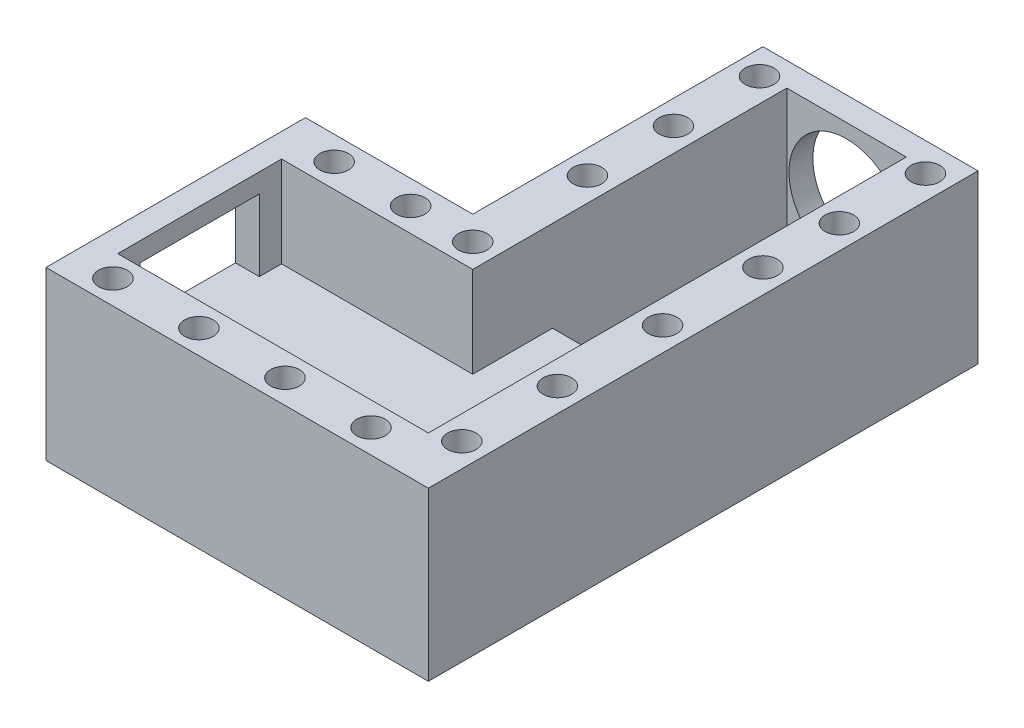
SolidWorks part; units mm, degrees
ref_plane "Спереди" through (0, 0, 0) normal (0, 0, 1) x (1, 0, 0)
ref_plane "Сверху" through (0, 0, 0) normal (0, 1, 0) x (1, 0, 0)
ref_plane "Справа" through (0, 0, 0) normal (1, 0, 0) x (0, 0, -1)
sketch "Эскиз1" plane through (0, 0, 0) normal (0, 1, 0) x (1, 0, 0)
  line L1 (-30, -18.4615) -> (35, -18.4615)
  line L2 (-30, -18.4615) -> (-30, 15.8242)
  line L3 (-30, 15.8242) -> (10, 15.8242)
  line L4 (35, -18.4615) -> (35, 21.5385)
  line L5 (-30, -18.4615) -> (35, 21.5385) construction
  line L6 (-30, 15.8242) -> (35, -18.4615) construction
  line L8 (35, 21.5385) -> (35, 81.5385)
  line L9 (35, 81.5385) -> (10, 81.5385)
  line L10 (10, 15.8242) -> (10, 81.5385)
  line L14 (-25.9919, 25.8242) -> (0, 25.8242)
  line L15 (0, 25.8242) -> (0, 86.5385)
  line L19 (0, 86.5385) -> (45, 86.5385)
  line L20 (45, 86.5385) -> (45, -28.4615)
  line L21 (45, -28.4615) -> (-35, -28.4615)
  line L22 (-35, -28.4615) -> (-35, 25.8242)
  line L23 (-35, 25.8242) -> (-25.9919, 25.8242)
  point P0 (0, 0)
  dimension "D1" = 40
  dimension "D2" = 65
  dimension "D3" = 60
  dimension "D4" = 25
  dimension "D5" = 10
  dimension "D6" = 5
  dimension "D7" = 10
  dimension "D8" = 10
  dimension "D9" = 5
  dimension "D10" = 10
extrude "Бобышка-Вытянуть1" add sketch "Эскиз1" along normal blind 35
sketch "Эскиз3" plane through (0, 0, 0) normal (0, -1, 0) x (1, 0, 0)
  line L0 (35, -81.5385) -> (35, 18.4615)
  line L1 (35, 18.4615) -> (-30, 18.4615)
  line L2 (-30, 18.4615) -> (-30, -15.8242)
  line L3 (-30, -15.8242) -> (10, -15.8242)
  line L4 (10, -15.8242) -> (10, -81.5385)
  line L5 (10, -81.5385) -> (35, -81.5385)
extrude "Бобышка-Вытянуть2" add sketch "Эскиз3" against normal blind 5
sketch "Эскиз4" plane through (0, 35, 0) normal (0, 1, 0) x (1, 0, 0)
  line L0 (35, 81.5385) -> (35, -28.4615) construction
  line L1 (-35, -28.4615) -> (45, -28.4615) construction
  line L2 (35, -28.4615) -> (35, 86.5385) construction
  line L3 (45, 86.5385) -> (0, 86.5385) construction
  line L4 (35, 86.5385) -> (45, 86.5385) construction
  line L5 (35, -28.4615) -> (45, -28.4615) construction
  line L6 (35, -18.4615) -> (-35, -18.4615) construction
  line L7 (35, -18.4615) -> (-30, -18.4615) construction
  line L8 (-35, 25.8242) -> (-35, -28.4615) construction
  line L9 (-35, -18.4615) -> (-35, -28.4615) construction
  line L10 (-35, -23.4615) -> (45, -23.4615) construction
  line L11 (45, -28.4615) -> (45, 86.5385) construction
  line L12 (40, 86.5385) -> (40, -28.4615) construction
  line L13 (10, 15.8242) -> (10, 86.5385) construction
  line L14 (10, 86.5385) -> (0, 86.5385) construction
  line L15 (0, 86.5385) -> (0, 15.8242) construction
  line L16 (10, 15.8242) -> (-30, 15.8242) construction
  line L17 (0, 15.8242) -> (10, 15.8242) construction
  line L18 (10, 15.8242) -> (-35, 15.8242) construction
  line L19 (-35, 15.8242) -> (-35, 25.8242) construction
  line L20 (-35, 25.8242) -> (10, 25.8242) construction
  line L21 (5, 86.5385) -> (5, 15.8242) construction
  line L22 (-35, 20.8242) -> (10, 20.8242) construction
  circle A0 centre (40, 80.5385) radius 3
  circle A1 centre (40, 62.5385) radius 3
  circle A2 centre (40, 46.5385) radius 3
  circle A3 centre (40, 25.5385) radius 3
  circle A4 centre (40, 3.5385) radius 3
  circle A5 centre (40, -16.4615) radius 3
  circle A6 centre (5, 80.8242) radius 3
  circle A7 centre (5, 62.8242) radius 3
  circle A8 centre (5, 44.8242) radius 3
  circle A9 centre (-24, 20.8242) radius 3
  circle A10 centre (-8, 20.8242) radius 3
  circle A11 centre (5, 20.8242) radius 3
  circle A12 centre (-26, -23.4615) radius 3
  circle A13 centre (-8, -23.4615) radius 3
  circle A14 centre (10, -23.4615) radius 3
  circle A15 centre (28, -23.4615) radius 3
  dimension "D1" = 6
  dimension "D2" = 6
  dimension "D3" = 6
  dimension "D4" = 6
  dimension "D5" = 6
  dimension "D6" = 18
  dimension "D7" = 18
  dimension "D8" = 13
  dimension "D9" = 16
  dimension "D10" = 18
  dimension "D11" = 16
  dimension "D12" = 21
  dimension "D13" = 22
  dimension "D14" = 20
  dimension "D15" = 18
  dimension "D16" = 18
  dimension "D17" = 18
  dimension "D18" = 12
  dimension "D19" = 17
  dimension "D21" = 5
  dimension "D22" = 24
  dimension "D20" = 5
extrude "Вырез-Вытянуть1" cut sketch "Эскиз4" against normal blind 20
sketch "Эскиз6" plane through (0, 5, 0) normal (0, 1, 0) x (1, 0, 0)
  line L0 (35, 81.5385) -> (35, -18.4615) construction
  line L1 (10, 15.8242) -> (35, 15.8242)
  line L2 (10, 15.8242) -> (10, 32.5031)
  line L3 (10, 32.5031) -> (35, 32.5031)
  line L4 (35, 15.8242) -> (35, 32.5031)
extrude "Бобышка-Вытянуть3" add sketch "Эскиз6" along normal blind 11
sketch "Эскиз7" plane through (0, 5, 0) normal (0, 1, 0) x (1, 0, 0)
  line L1 (35, 15.8242) -> (-30, 15.8242)
  line L2 (35, 15.8242) -> (35, -18.4615)
  line L3 (35, -18.4615) -> (-30, -18.4615)
  line L4 (-30, 15.8242) -> (-30, -18.4615)
extrude "Бобышка-Вытянуть4" add sketch "Эскиз7" along normal blind 11
sketch "Эскиз8" plane through (0, 0, -81.5385) normal (0, 0, 1) x (1, 0, 0)
  line L0 (22.5, 35) -> (22.5, 5) construction
  line L1 (35, 35) -> (10, 35) construction
  line L2 (10, 5) -> (35, 5) construction
  circle A0 centre (22.5, 20) radius 12.0525
extrude "Вырез-Вытянуть2" cut sketch "Эскиз8" against normal blind 11
sketch "Эскиз9" plane through (-30, 0, 0) normal (1, 0, 0) x (0, 0, -1)
  line L0 (-1.3187, 35) -> (-1.3187, 16) construction
  line L1 (15.8242, 35) -> (-18.4615, 35) construction
  line L2 (15.8242, 16) -> (-18.4615, 16) construction
  line L4 (-13.8187, 31) -> (11.1813, 31)
  line L5 (-13.8187, 31) -> (-13.8187, 16)
  line L6 (-13.8187, 16) -> (11.1813, 16)
  line L7 (11.1813, 31) -> (11.1813, 16)
  line L8 (-13.8187, 31) -> (11.1813, 16) construction
  line L9 (-13.8187, 16) -> (11.1813, 31) construction
  point P6 (-1.3187, 23.5)
  dimension "D1" = 15
  dimension "D2" = 25
extrude "Вырез-Вытянуть3" cut sketch "Эскиз9" against normal blind 11
